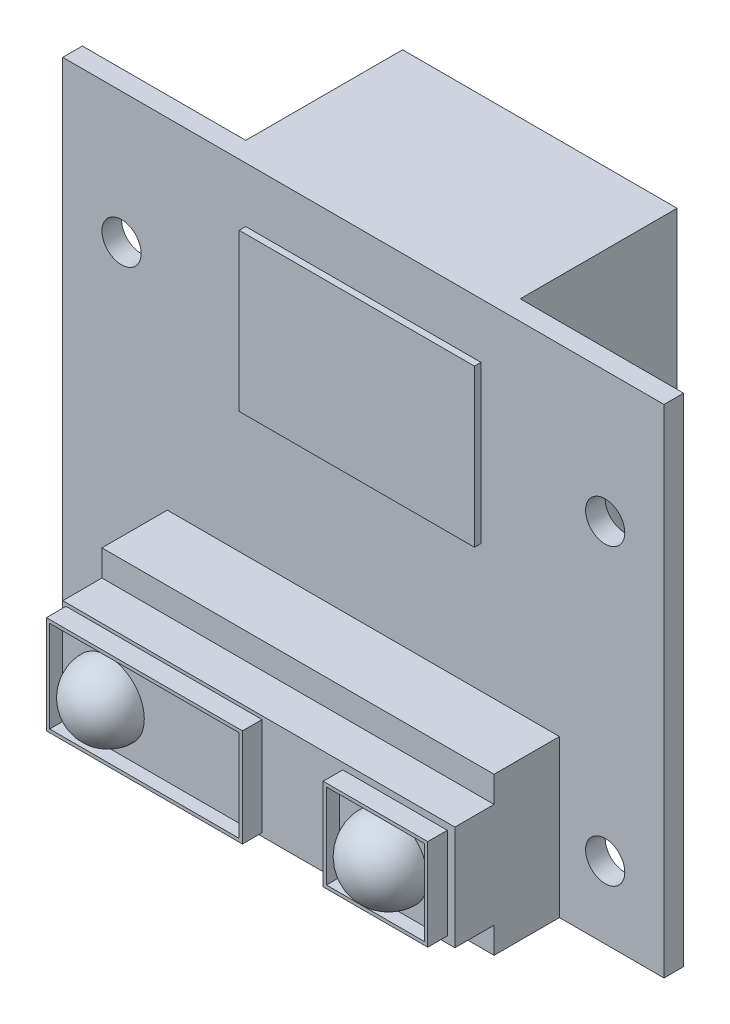
SolidWorks part; units mm, degrees
ref_plane "Front Plane" through (0, 0, 0) normal (0, 0, 1) x (1, 0, 0)
ref_plane "Top Plane" through (0, 0, 0) normal (0, 1, 0) x (1, 0, 0)
ref_plane "Right Plane" through (0, 0, 0) normal (1, 0, 0) x (0, 0, -1)
ref_plane "Plane1" through (0, 0, 0) normal (0, 0, 1) x (1, 0, 0)
ref_plane "Plane2" through (0, 0, 0) normal (0, 1, 0) x (1, 0, 0)
ref_plane "Plane3" through (0, 0, 0) normal (1, 0, 0) x (0, 0, -1)
ref_plane "Plane6" through (0, 0, 10) normal (0, 0, 1) x (1, 0, 0)
sketch "Sketch2" plane through (0, 0, 0) normal (0, 0, 1) x (1, 0, 0)
  line L1 (0, 0) -> (46, 0)
  line L2 (0, 0) -> (0, 38)
  line L3 (0, 38) -> (46, 38)
  line L4 (46, 0) -> (46, 38)
  circle A0 centre (4.5, 28) radius 1.5
  circle A1 centre (4.5, 5.5) radius 1.5
  circle A2 centre (41.5, 5.5) radius 1.5
  circle A3 centre (41.5, 28) radius 1.5
  dimension "D3" = 3
  dimension "D4" = 22.5
  dimension "D5" = 22.5
  dimension "D7" = 4.5
  dimension "D8" = 10
  dimension "D9" = 10
  dimension "D1" = 46
  dimension "D2" = 38
  dimension "D6" = 4.5
extrude "Boss-Extrude1" add sketch "Sketch2" along normal blind 1.5
sketch "Sketch3" plane through (0, 0, 0) normal (0, 0, 1) x (1, 0, 0)
  line L0 (0.825, 0) -> (-0.825, 0) construction
  line L1 (8, 0) -> (38, 0)
  line L2 (8, 0) -> (8, 12)
  line L3 (8, 12) -> (38, 12)
  line L4 (38, 0) -> (38, 12)
  line L5 (46, 0) -> (46, 38) construction
  dimension "D4" = 8
  dimension "D1" = 30
  dimension "D2" = 12
  dimension "D3" = 0
extrude "Boss-Extrude2" add sketch "Sketch3" along normal blind 6.5
sketch "Sketch4" plane through (0, 0, 0) normal (0, 0, 1) x (1, 0, 0)
  line L0 (8, 12) -> (8, 0) construction
  line L1 (8, 2) -> (38, 2)
  line L2 (8, 2) -> (8, 10)
  line L3 (8, 10) -> (38, 10)
  line L4 (38, 2) -> (38, 10)
  line L5 (38, 12) -> (8, 12) construction
  dimension "D1" = 8
  dimension "D2" = 30
  dimension "D3" = 2
extrude "Boss-Extrude3" add sketch "Sketch4" along normal blind 9.5
sketch "Sketch5" plane through (0, 0, 0) normal (0, 0, 1) x (1, 0, 0)
  line L1 (8.25, 9.75) -> (23.25, 9.75)
  line L2 (8.25, 9.75) -> (8.25, 2.25)
  line L3 (8.25, 2.25) -> (23.25, 2.25)
  line L4 (23.25, 9.75) -> (23.25, 2.25)
  line L5 (38, 10) -> (8, 10) construction
  line L6 (8, 10) -> (8, 2) construction
  dimension "D1" = 15
  dimension "D2" = 7.5
  dimension "D3" = 0.25
  dimension "D4" = 0.25
extrude "Boss-Extrude4" add sketch "Sketch5" along normal blind 11
sketch "Sketch6" plane through (0, 0, 10) normal (0, 0, 1) x (1, 0, 0)
  line L0 (23.25, 2.25) -> (23.25, 9.75) construction
  line L1 (8.5, 9.5) -> (23, 9.5)
  line L2 (8.5, 9.5) -> (8.5, 2.5)
  line L3 (8.5, 2.5) -> (23, 2.5)
  line L4 (23, 9.5) -> (23, 2.5)
  line L5 (23.25, 9.75) -> (8.25, 9.75) construction
  line L9 (8.25, 9.75) -> (8.25, 2.25) construction
  dimension "D1" = 0.25
  dimension "D2" = 0.25
  dimension "D3" = 7
  dimension "D4" = 0.25
extrude "Cut-Extrude1" cut sketch "Sketch6" along normal blind 11
sketch "Sketch7" plane through (0, 0, 10) normal (0, 0, 1) x (1, 0, 0)
  line L0 (11.9562, 5.7869) -> (11.9562, 32.2131) construction
  circle A0 centre (11.9562, 5.7869) radius 2.7833
surface "Surface-Revolve1" sketch "Sketch7" parameters "D1"=360
sketch "Sketch9" plane through (0, 0, 0) normal (0, 0, 1) x (1, 0, 0)
  line L0 (38, 10) -> (8, 10) construction
  line L1 (29.4246, 9.5) -> (37.4246, 9.5)
  line L2 (29.4246, 9.5) -> (29.4246, 2.5)
  line L3 (29.4246, 2.5) -> (37.4246, 2.5)
  line L4 (37.4246, 9.5) -> (37.4246, 2.5)
  dimension "D1" = 7
  dimension "D2" = 8
  dimension "0.5" = 0.5
extrude "Boss-Extrude5" add sketch "Sketch9" along normal blind 11
sketch "Sketch10" plane through (0, 0, 10) normal (0, 0, 1) x (1, 0, 0)
  line L0 (37.4246, 2.5) -> (37.4246, 9.5) construction
  line L1 (29.6746, 9.25) -> (37.1746, 9.25)
  line L2 (29.6746, 9.25) -> (29.6746, 2.75)
  line L3 (29.6746, 2.75) -> (37.1746, 2.75)
  line L4 (37.1746, 9.25) -> (37.1746, 2.75)
  line L5 (29.4246, 2.5) -> (37.4246, 2.5) construction
  line L6 (37.4246, 9.5) -> (29.4246, 9.5) construction
  line L7 (29.4246, 9.5) -> (29.4246, 2.5) construction
  dimension "D1" = 0.25
  dimension "D2" = 0.25
  dimension "D3" = 0.25
  dimension "D4" = 0.25
extrude "Cut-Extrude2" cut sketch "Sketch10" along normal blind 11
sketch "Sketch11" plane through (0, 0, 10) normal (0, 0, 1) x (1, 0, 0)
  line L0 (29.6746, 9.25) -> (37.1746, 9.25) construction
  line L1 (33.424, 6) -> (33.424, 19.0845) construction
  circle A0 centre (33.424, 6) radius 3
  dimension "D1" = 6
  dimension "D2" = 3.25
surface "Surface-Revolve2" sketch "Sketch11" parameters "D1"=360
sketch "Sketch12" plane through (0, 0, 0) normal (0, 0, 1) x (1, 0, 0)
  line L0 (46, 38) -> (0, 38) construction
  line L1 (33.5, 38) -> (12.5, 38)
  line L2 (33.5, 38) -> (33.5, 18)
  line L3 (33.5, 18) -> (12.5, 18)
  line L4 (12.5, 38) -> (12.5, 18)
  line L5 (0, -7.15) -> (0, 7.15) construction
  dimension "D1" = 21
  dimension "D2" = 12.5
  dimension "D3" = 20
extrude "Boss-Extrude6" add sketch "Sketch12" against normal blind 12
sketch "Sketch13" plane through (0, 0, 0) normal (0, 0, 1) x (1, 0, 0)
  line L1 (14, 33.7891) -> (32, 33.7891)
  line L2 (14, 33.7891) -> (14, 21.7891)
  line L3 (14, 21.7891) -> (32, 21.7891)
  line L4 (32, 33.7891) -> (32, 21.7891)
  line L5 (46, 0) -> (46, 38) construction
  dimension "D1" = 12
  dimension "D2" = 18
  dimension "D3" = 14
extrude "Boss-Extrude7" add sketch "Sketch13" along normal blind 2
